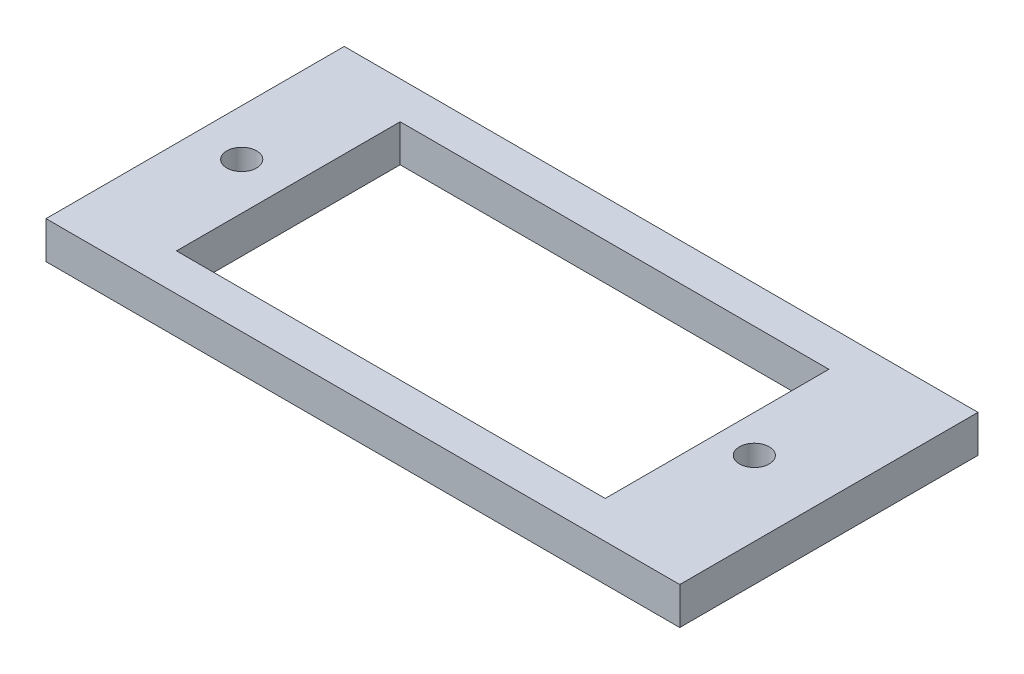
SolidWorks part; units mm, degrees
ref_plane "Front Plane" through (0, 0, 0) normal (0, 0, 1) x (1, 0, 0)
ref_plane "Top Plane" through (0, 0, 0) normal (0, 1, 0) x (1, 0, 0)
ref_plane "Right Plane" through (0, 0, 0) normal (1, 0, 0) x (0, 0, -1)
sketch "Sketch1" plane through (0, 0, 0) normal (0, 1, 0) x (1, 0, 0)
  line L1 (17, -8) -> (-17, -8)
  line L2 (17, -8) -> (17, 8)
  line L3 (17, 8) -> (-17, 8)
  line L4 (-17, -8) -> (-17, 8)
  line L5 (17, -8) -> (-17, 8) construction
  line L6 (17, 8) -> (-17, -8) construction
  point P0 (0, 0)
  dimension "D1" = 16
  dimension "D2" = 34
extrude "Boss-Extrude1" add sketch "Sketch1" along normal blind 2
sketch "Sketch2" plane through (0, 2, 0) normal (0, 1, 0) x (1, 0, 0)
  line L0 (-1000, 0) -> (49000, 0) construction
  line L1 (0, -1000) -> (0, 49000) construction
  line L2 (-17, 8) -> (-17, -8) construction
  line L3 (11, -6) -> (-12, -6)
  line L4 (11, -6) -> (11, 6)
  line L5 (11, 6) -> (-12, 6)
  line L6 (-12, -6) -> (-12, 6)
  line L7 (11, -6) -> (-12, 6) construction
  line L8 (11, 6) -> (-12, -6) construction
  point P5 (-0.5, 0)
  dimension "D1" = 12
  dimension "D2" = 23
  dimension "D3" = 5
extrude "Cut-Extrude1" cut sketch "Sketch2" against normal through all both and the other way through all
sketch "Sketch3" plane through (0, 0, 0) normal (0, 1, 0) x (1, 0, 0)
  line L0 (-1000, 0) -> (49000, 0) construction
  line L1 (-12, 6) -> (-12, -6) construction
  line L3 (11, -6) -> (11, 6) construction
  circle A0 centre (-14.5, 0) radius 0.8
  circle A1 centre (13, 0) radius 0.8
  dimension "D1" = 1.6
  dimension "D3" = 1.6
  dimension "D2" = 2.5
  dimension "D4" = 2
extrude "Cut-Extrude5" cut sketch "Sketch3" along normal blind 2
